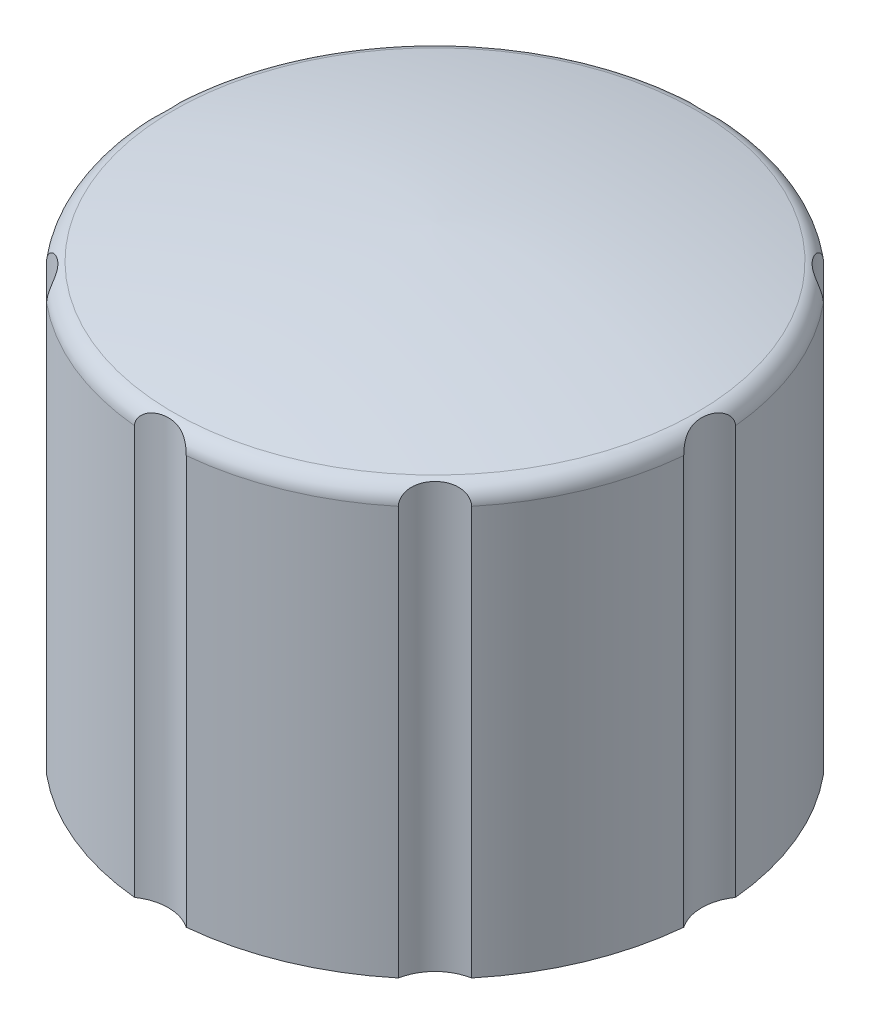
SolidWorks part; units mm, degrees
ref_plane "Front Plane" through (0, 0, 0) normal (0, 0, 1) x (1, 0, 0)
ref_plane "Top Plane" through (0, 0, 0) normal (0, 1, 0) x (1, 0, 0)
ref_plane "Right Plane" through (0, 0, 0) normal (1, 0, 0) x (0, 0, -1)
sketch "Sketch1" plane through (0, 0, 0) normal (0, 0, 1) x (1, 0, 0)
  line L0 (0, 0) -> (0, 15250.1234) construction
  line L1 (-15, 19) -> (-15, -4)
  line L2 (-15, -4) -> (-12, -4)
  line L3 (-12, -4) -> (-12, 16)
  line L4 (-12, 16) -> (-5, 16)
  line L5 (-5, 16) -> (-5, 0)
  line L6 (-5, 0) -> (0, 0)
  line L7 (0, 0) -> (0, 21)
  arc A0 (-15, 19) -> (0, 21) centre (1.6973, -48.9794) cw
  dimension "D1" = 30
  dimension "D8" = 70
  dimension "D2" = 16
  dimension "D3" = 10
  dimension "D4" = 3
  dimension "D5" = 5
  dimension "D6" = 3
  dimension "D7" = 20
revolve "Revolve1" add sketch "Sketch1" angle 360 about L0
fillet "Fillet1" radius 1 1 edges at (0, 19, -15)
sketch "Sketch2" plane through (0, -4, 0) normal (0, -1, 0) x (1, 0, 0)
  circle A0 centre (-17, 0) radius 2.5
  circle A1 centre (0, 0) radius 5 construction
  circle A2 centre (-12.0208, 12.0208) radius 2.5
  circle A3 centre (0, 17) radius 2.5
  circle A4 centre (12.0208, 12.0208) radius 2.5
  circle A5 centre (17, 0) radius 2.5
  circle A6 centre (12.0208, -12.0208) radius 2.5
  circle A7 centre (0, -17) radius 2.5
  circle A8 centre (-12.0208, -12.0208) radius 2.5
  circle A9 centre (0, 0) radius 17 construction
  point P4 (0, 0)
  point P22 (0, 0)
  point P24 (0, 0)
  dimension "D1" = 17
  dimension "D2" = 5
  dimension "D3" = 8
extrude "Cut-Extrude1" cut sketch "Sketch2" against normal through all
